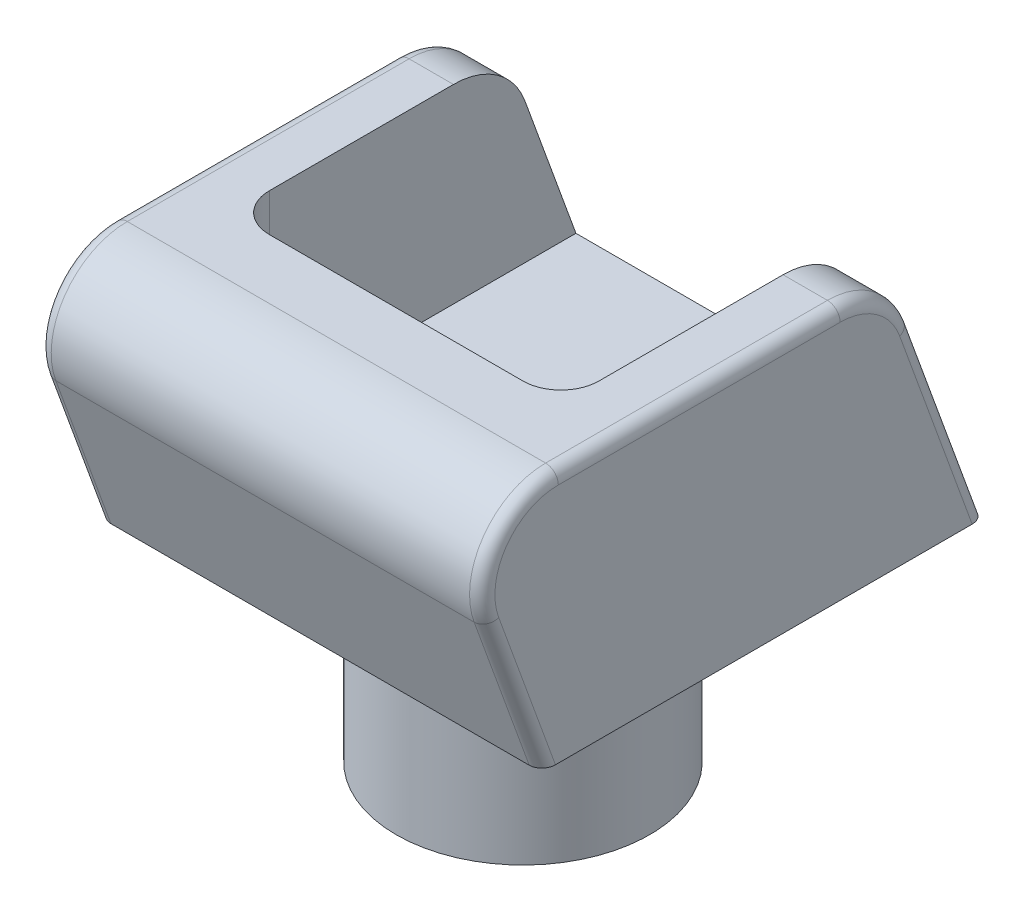
SolidWorks part; units mm, degrees
ref_plane "Front Plane" through (0, 0, 0) normal (0, 0, 1) x (1, 0, 0)
ref_plane "Top Plane" through (0, 0, 0) normal (0, 1, 0) x (1, 0, 0)
ref_plane "Right Plane" through (0, 0, 0) normal (1, 0, 0) x (0, 0, -1)
sketch "Sketch1" plane through (0, 0, 0) normal (1, 0, 0) x (0, 0, -1)
  line L0 (0, 0) -> (-7.2794, 20)
  line L1 (-7.2794, 20) -> (27.7206, 20)
  line L2 (27.7206, 20) -> (35, 0)
  line L3 (35, 0) -> (0, 0)
  dimension "D1" = 20
  dimension "D2" = 35
  dimension "D3" = 110
extrude "Boss-Extrude1" add sketch "Sketch1" along normal mid plane 35
sketch "Sketch2" plane through (0, 0, 0) normal (1, 0, 0) x (0, 0, -1)
  line L0 (6, 20) -> (6, 5)
  line L1 (6, 5) -> (33.1801, 5)
  line L2 (33.1801, 5) -> (27.7206, 20)
  line L3 (27.7206, 20) -> (6, 20)
  line L4 (0, 0) -> (35, 0) construction
  line L6 (27.7206, 20) -> (-7.2794, 20) construction
  line L7 (35, 0) -> (27.7206, 20) construction
  dimension "D1" = 5
  dimension "D2" = 6
extrude "Cut-Extrude1" cut sketch "Sketch2" against normal mid plane 26
fillet "Fillet1" radius 6 3 edges at (-15.25, 20, -27.7206) (15.25, 20, -27.7206) (0, 20, 7.2794)
fillet "Fillet2" radius 1 10 edges at (-17.5, 5.9739, 2.1743) (-17.5, 17.4415, 3.6254) (-17.5, 20, -12.4044) (-17.5, 18.9149, -26.9608) (17.5, 5.9739, 2.1743) (17.5, 17.4415, 3.6254) (17.5, 20, -12.4044) (17.5, 18.9149, -26.9608) (-17.5, 8.0261, -32.0788) (17.5, 8.0261, -32.0788)
fillet "Fillet3" radius 3 2 edges at (-13, 12.5, -6) (13, 12.5, -6)
sketch "Sketch3" plane through (0, 0, 0) normal (0, -1, 0) x (1, 0, 0)
  line L0 (16.5, 0) -> (-16.5, 0) construction
  circle A0 centre (0, -16) radius 10
  circle A1 centre (0, -16) radius 7
  dimension "D1" = 20
  dimension "D2" = 16
  dimension "D3" = 3
extrude "Boss-Extrude2" add sketch "Sketch3" along normal blind 16
sketch "Sketch4" plane through (0, 0, 0) normal (1, 0, 0) x (0, 0, -1)
  line L0 (6, -8) -> (26, -8) construction
  line L1 (6, 0) -> (6, -16) construction
  line L2 (26, -16) -> (26, 0) construction
  line L3 (6, -16) -> (26, -16) construction
  circle A0 centre (16, -8) radius 1.5
  point P10 (16, -8)
  dimension "D1" = 3
  dimension "D2" = 8
extrude "Cut-Extrude2" cut sketch "Sketch4" against normal blind 16
sketch "Sketch5" plane through (-17.5, 0, 0) normal (-1, 0, 0) x (0, 0, 1)
  text T0 "Designed By: Omkar Shrivardhankar" font "Century Gothic" height in points 4
extrude "Boss-Extrude3" add sketch "Sketch5" along normal blind 0.3
